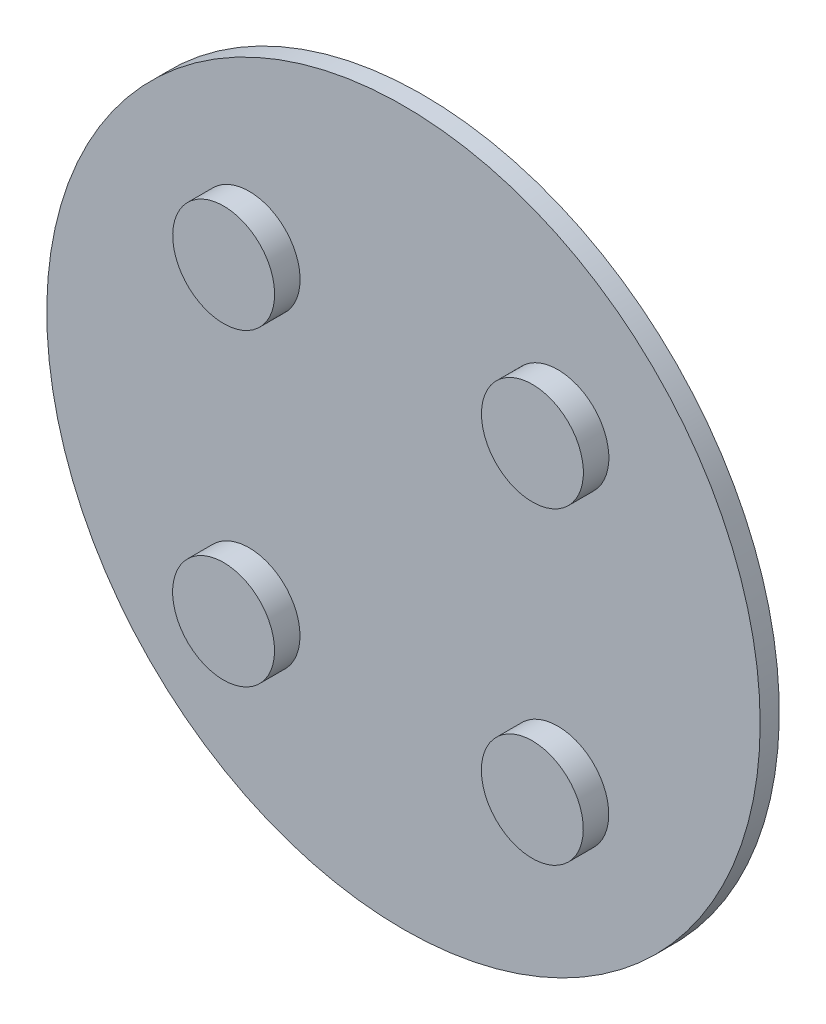
SolidWorks part; units mm, degrees
ref_plane "Front Plane" through (0, 0, 0) normal (0, 0, 1) x (1, 0, 0)
ref_plane "Top Plane" through (0, 0, 0) normal (0, 1, 0) x (1, 0, 0)
ref_plane "Right Plane" through (0, 0, 0) normal (1, 0, 0) x (0, 0, -1)
sketch "Sketch1" plane through (0, 0, 0) normal (0, 0, 1) x (1, 0, 0)
  circle A0 centre (-32.8192, -16.9399) radius 200
extrude "Boss-Extrude1" add sketch "Sketch1" along normal blind 15
sketch "Sketch2" plane through (0, 0, 15) normal (0, 0, 1) x (1, 0, 0)
  line L1 (-105.2972, 2.9682) -> (43.4081, 2.9682)
  line L2 (-105.2972, 2.9682) -> (-105.2972, -47.0004)
  line L3 (-105.2972, -47.0004) -> (43.4081, -47.0004)
  line L4 (43.4081, 2.9682) -> (43.4081, -47.0004)
extrude "Boss-Extrude2" add sketch "Sketch2" along normal blind 20
sketch "Sketch3" plane through (0, 2.9682, 0) normal (0, 1, 0) x (1, 0, 0)
  arc A0 (-28.8775, -22.677) -> (-28.8775, -26.8363) centre (-36.6024, -24.7567) ccw
  arc A1 (-28.8775, -26.8363) -> (-28.8775, -22.677) centre (-21.1525, -24.7567) ccw
extrude "Cut-Extrude2" cut sketch "Sketch3" against normal blind 103
sketch "Sketch4" plane through (0, 0, 35) normal (0, 0, 1) x (1, 0, 0)
  circle A0 centre (-32.8192, -25.1684) radius 280
extrude "Boss-Extrude3" add sketch "Sketch4" along normal blind 15
sketch "Sketch6" plane through (0, 0, 50) normal (0, 0, 1) x (1, 0, 0)
  circle A0 centre (-154.0323, -146.3093) radius 40
extrude "Boss-Extrude4" add sketch "Sketch6" along normal blind 20 contours A0
pattern_circular "CirPattern1" count 4 over 360 about axis through (-32.8192, -25.1684, 0) along (0, 0, 1) of "Boss-Extrude4"
sketch "Sketch7" plane through (0, 0, 35) normal (0, 0, -1) x (-1, 0, 0)
  line L1 (-30.0382, -217.8623) -> (122.3958, -217.8623)
  line L2 (-30.0382, -217.8623) -> (-30.0382, -290.4532)
  line L3 (-30.0382, -290.4532) -> (122.3958, -290.4532)
  line L4 (122.3958, -217.8623) -> (122.3958, -290.4532)
  circle A0 centre (32.8192, -25.1684) radius 280 construction
extrude "Boss-Extrude5" add sketch "Sketch7" along normal blind 5
